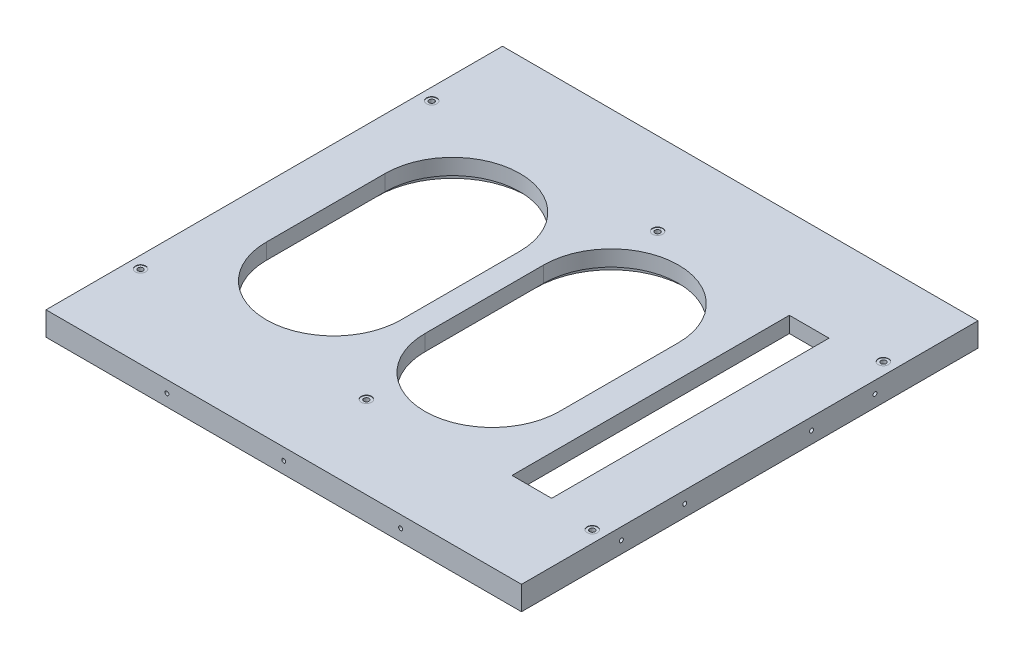
SolidWorks part; units mm, degrees
material "灰铸铁"
ref_plane "前视基准面" through (0, 0, 0) normal (0, 0, 1) x (1, 0, 0)
ref_plane "上视基准面" through (0, 0, 0) normal (0, 1, 0) x (1, 0, 0)
ref_plane "右视基准面" through (0, 0, 0) normal (1, 0, 0) x (0, 0, -1)
sketch "草图1" plane through (0, 0, 0) normal (0, 1, 0) x (1, 0, 0)
  line L1 (-300, -288) -> (300, -288)
  line L2 (-300, -288) -> (-300, 288)
  line L3 (-300, 288) -> (300, 288)
  line L4 (300, -288) -> (300, 288)
  line L5 (-300, -288) -> (300, 288) construction
  line L6 (-300, 288) -> (300, -288) construction
  point P0 (0, 0)
  dimension "D1" = 600
  dimension "D2" = 576
extrude "凸台-拉伸1" add sketch "草图1" along normal blind 30
sketch "草图2" plane through (0, 0, 0) normal (0, -1, 0) x (1, 0, 0)
  line L0 (-245, 75) -> (-245, -75)
  line L1 (300, 288) -> (300, -288) construction
  line L2 (165, 185) -> (235, 185)
  line L3 (165, 185) -> (165, -185)
  line L4 (165, -185) -> (235, -185)
  line L5 (235, 185) -> (235, -185)
  line L6 (165, 185) -> (235, -185) construction
  line L7 (165, -185) -> (235, 185) construction
  line L8 (-300, 288) -> (300, 288) construction
  line L9 (-55, 75) -> (-55, -75)
  line L11 (-45, 75) -> (-45, -75)
  line L13 (145, 75) -> (145, -75)
  arc A0 (-45, -75) -> (145, -75) centre (50, -75) ccw
  arc A1 (145, 75) -> (-45, 75) centre (50, 75) ccw
  arc A2 (-245, -75) -> (-55, -75) centre (-150, -75) ccw
  arc A3 (-55, 75) -> (-245, 75) centre (-150, 75) ccw
  point P2 (200, 0)
  dimension "D5" = 95
  dimension "D7" = 250
  dimension "D1" = 70
  dimension "D2" = 370
  dimension "D3" = 100
  dimension "D4" = 288
  dimension "D6" = 150
  dimension "D8" = 213
  dimension "D9" = 2
extrude "切除-拉伸1" cut sketch "草图2" against normal blind 10
sketch "草图3" plane through (0, 10, 0) normal (0, -1, 0) x (1, 0, 0)
  line L0 (-35, 75) -> (-35, -75)
  line L1 (135, 75) -> (135, -75)
  line L2 (-65, 75) -> (-65, -75)
  line L3 (-235, 75) -> (-235, -75)
  line L4 (235, -185) -> (235, 185) construction
  line L5 (175, 175) -> (225, 175)
  line L6 (175, 175) -> (175, -175)
  line L7 (175, -175) -> (225, -175)
  line L8 (225, 175) -> (225, -175)
  line L9 (175, 175) -> (225, -175) construction
  line L10 (175, -175) -> (225, 175) construction
  arc A0 (135, 75) -> (-35, 75) centre (50, 75) ccw
  arc A1 (-35, -75) -> (135, -75) centre (50, -75) ccw
  arc A2 (-235, -75) -> (-65, -75) centre (-150, -75) ccw
  arc A3 (-65, 75) -> (-235, 75) centre (-150, 75) ccw
  point P1 (200, 0)
  dimension "D1" = 170
  dimension "D2" = 170
  dimension "D3" = 150
  dimension "D4" = 150
  dimension "D6" = 50
  dimension "D7" = 350
  dimension "D8" = 35
  dimension "D5" = 2
extrude "切除-拉伸2" cut sketch "草图3" against normal through all
sketch "草图9" plane through (0, 0, 0) normal (0, -1, 0) x (1, 0, 0)
  line L1 (-294, 264.5) -> (294, 264.5) construction
  line L2 (-294, 264.5) -> (-294, -264.5) construction
  line L3 (-294, -264.5) -> (294, -264.5) construction
  line L4 (294, 264.5) -> (294, -264.5) construction
  line L5 (-294, 264.5) -> (294, -264.5) construction
  line L6 (-294, -264.5) -> (294, 264.5) construction
  line L7 (-294, 223.5) -> (294, 223.5) construction
  line L8 (-294, 223.5) -> (-294, -223.5) construction
  line L9 (-294, -223.5) -> (294, -223.5) construction
  line L10 (294, 223.5) -> (294, -223.5) construction
  line L11 (-294, 223.5) -> (294, -223.5) construction
  line L12 (-294, -223.5) -> (294, 223.5) construction
  point P0 (0, 0)
  point P6 (0, 0)
  dimension "D1" = 588
  dimension "D2" = 529
  dimension "D3" = 447
  dimension "D4" = 588
hole_wizard "M6 螺纹孔1" positions "草图10" profile "草图11" tap size "M6" standard "GB"
sketch "草图10" plane through (0, 0, 0) normal (0, -1, 0) x (-1, 0, 0)
  point P0 (294, -264.5)
  point P3 (294, -223.5)
  point P6 (-294, -264.5)
  point P9 (-294, -223.5)
  point P12 (-294, 264.5)
  point P15 (-294, 223.5)
  point P18 (294, 223.5)
  point P21 (294, 264.5)
sketch "草图11" plane through (-294, 0, 264.5) normal (1, 0, 0) x (0, 0, -1)
  line L0 (0, 0) -> (0, 18.8026)
  line L1 (0, 18.8026) -> (3, 17)
  line L2 (3, 17) -> (3, 0)
  line L5 (3, 0) -> (0, 0)
  line L10 (0, 18.8026) -> (-3, 17) construction
  line L11 (0, -6.35) -> (0, 107.95) construction
  dimension "螺纹孔钻头直径" = 6
  dimension "螺纹孔钻头深度" = 17
  dimension "导头角度" = 118
cosmetic thread "孔螺蚊线1" parameters "D1"=12, "D2"=6
cosmetic thread "孔螺蚊线2" parameters "D1"=12, "D2"=6
cosmetic thread "孔螺蚊线3" parameters "D1"=12, "D2"=6
cosmetic thread "孔螺蚊线4" parameters "D1"=12, "D2"=6
cosmetic thread "孔螺蚊线5" parameters "D1"=12, "D2"=6
cosmetic thread "孔螺蚊线6" parameters "D1"=12, "D2"=6
cosmetic thread "孔螺蚊线7" parameters "D1"=12, "D2"=6
cosmetic thread "孔螺蚊线8" parameters "D1"=12, "D2"=6
sketch "草图16" plane through (0, 0, -288) normal (0, 0, -1) x (-1, 0, 0)
  line L0 (-300, 30) -> (300, 30) construction
  line L1 (-300, 30) -> (-300, 0) construction
  point P0 (-147.5, 15)
  point P7 (0, 15)
  point P8 (147.5, 15)
  dimension "D1" = 15
  dimension "D2" = 152.5
  dimension "D3" = 3
hole_wizard "M6 螺纹孔2" positions "草图17" profile "草图19" tap size "M6" standard "GB"
sketch "草图17" plane through (0, 0, -288) normal (0, 0, -1) x (-1, 0, 0)
  point P0 (-147.5, 15)
  point P3 (0, 15)
  point P6 (147.5, 15)
sketch "草图19" plane through (147.5, 15, -288) normal (1, 0, 0) x (0, 1, 0)
  line L0 (0, 0) -> (0, 11.5022)
  line L1 (0, 11.5022) -> (2.5, 10)
  line L2 (2.5, 10) -> (2.5, 0)
  line L5 (2.5, 0) -> (0, 0)
  line L10 (0, 11.5022) -> (-2.5, 10) construction
  line L11 (0, -6.35) -> (0, 107.95) construction
  dimension "螺纹孔钻头直径" = 5
  dimension "螺纹孔钻头深度" = 10
  dimension "导头角度" = 118
cosmetic thread "孔螺蚊线9" parameters "D1"=12, "D2"=6
cosmetic thread "孔螺蚊线10" parameters "D1"=12, "D2"=6
cosmetic thread "孔螺蚊线11" parameters "D1"=12, "D2"=6
mirror "镜向1" about plane through (0, 0, 0) normal (0, 0, 1) of "M6 螺纹孔2"
cosmetic thread "孔螺蚊线12" parameters "D1"=12, "D2"=6
cosmetic thread "孔螺蚊线13" parameters "D1"=12, "D2"=6
cosmetic thread "孔螺蚊线14" parameters "D1"=12, "D2"=6
sketch "草图20" plane through (-300, 0, 0) normal (-1, 0, 0) x (0, 0, 1)
  line L0 (-288, 30) -> (-288, 0) construction
  line L4 (-288, 30) -> (288, 30) construction
  line L5 (-78, 15) -> (82, 15) construction
  line L6 (-158, 15) -> (162, 15) construction
  point P5 (0, 0)
  point P11 (2, 15)
  point P14 (2, 15)
  dimension "D1" = 160
  dimension "D2" = 15
  dimension "D3" = 320
  dimension "D4" = 15
  dimension "D5" = 290
  dimension "D6" = 290
hole_wizard "M6 螺纹孔3" positions "草图21" profile "草图22" tap size "M6" standard "GB"
sketch "草图21" plane through (-300, 0, 0) normal (-1, 0, 0) x (0, 0, 1)
  point P0 (-158, 15)
  point P3 (-78, 15)
  point P6 (82, 15)
  point P9 (162, 15)
  point P12 (0, 0)
sketch "草图22" plane through (-300, 15, -158) normal (0, 1, 0) x (0, 0, 1)
  line L0 (0, 0) -> (0, 16.5022)
  line L1 (0, 16.5022) -> (2.5, 15)
  line L2 (2.5, 15) -> (2.5, 0)
  line L5 (2.5, 0) -> (0, 0)
  line L10 (0, 16.5022) -> (-2.5, 15) construction
  line L11 (0, -6.35) -> (0, 107.95) construction
  dimension "螺纹孔钻头直径" = 5
  dimension "螺纹孔钻头深度" = 15
  dimension "导头角度" = 118
cosmetic thread "孔螺蚊线15" parameters "D1"=12, "D2"=6
cosmetic thread "孔螺蚊线16" parameters "D1"=12, "D2"=6
cosmetic thread "孔螺蚊线17" parameters "D1"=12, "D2"=6
cosmetic thread "孔螺蚊线18" parameters "D1"=12, "D2"=6
mirror "镜向2" about plane through (0, 0, 0) normal (1, 0, 0) of "M6 螺纹孔3"
cosmetic thread "孔螺蚊线19" parameters "D1"=12, "D2"=6
cosmetic thread "孔螺蚊线20" parameters "D1"=12, "D2"=6
cosmetic thread "孔螺蚊线21" parameters "D1"=12, "D2"=6
cosmetic thread "孔螺蚊线22" parameters "D1"=12, "D2"=6
sketch "草图23" plane through (0, 30, 0) normal (0, 1, 0) x (1, 0, 0)
  line L1 (-285, 183.68) -> (285, 183.68) construction
  line L2 (-285, 183.68) -> (-285, -183.68) construction
  line L3 (-285, -183.68) -> (285, -183.68) construction
  line L4 (285, 183.68) -> (285, -183.68) construction
  line L5 (-285, 183.68) -> (285, -183.68) construction
  line L6 (-285, -183.68) -> (285, 183.68) construction
  point P0 (0, 0)
  point P6 (0, 183.68)
  point P7 (0, -183.68)
  dimension "D1" = 570
  dimension "D2" = 367.36
hole_wizard "M6 六角头螺栓的柱形沉头孔1" positions "草图24" profile "草图26" counterbore size "M6" standard "GB" end condition through all
sketch "草图24" plane through (0, 30, 0) normal (0, 1, 0) x (1, 0, 0)
  point P0 (-285, 183.68)
  point P3 (0, 183.68)
  point P6 (285, 183.68)
  point P9 (-285, -183.68)
  point P12 (0, -183.68)
  point P15 (285, -183.68)
sketch "草图26" plane through (-285, 30, -183.68) normal (1, 0, 0) x (0, 0, 1)
  line L0 (0, 0) -> (0, 30)
  line L1 (0, 30) -> (3.3, 30)
  line L3 (3.3, 30) -> (3.3, 0.5)
  line L4 (3.3, 0.5) -> (6.5, 0.5)
  line L5 (6.5, 0.5) -> (6.5, 0)
  line L7 (6.5, 0) -> (0, 0)
  line L11 (0, -6.35) -> (0, 107.95) construction
  dimension "通孔孔直径" = 6.6
  dimension "通孔孔深度" = 30
  dimension "柱形沉头孔直径" = 13
  dimension "柱形沉头孔深度" = 0.5
